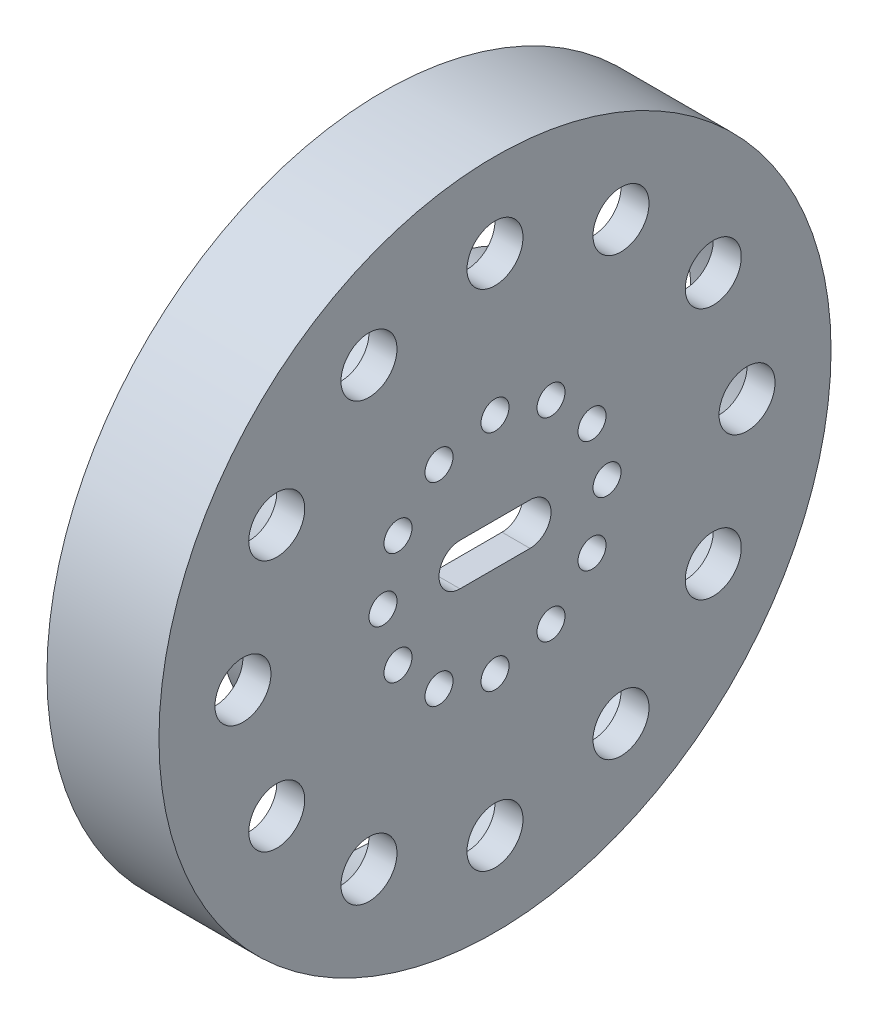
SolidWorks part; units mm, degrees
ref_plane "Front Plane" through (0, 0, 0) normal (0, 0, 1) x (1, 0, 0)
ref_plane "Top Plane" through (0, 0, 0) normal (0, 1, 0) x (1, 0, 0)
ref_plane "Right Plane" through (0, 0, 0) normal (1, 0, 0) x (0, 0, -1)
sketch "Sketch1" plane through (0, 0, 0) normal (0, 0, 1) x (1, 0, 0)
  line L12 (0, 0) -> (0, 76.2)
  line L13 (-25.4, 76.2) -> (0, 76.2)
  line L14 (-6.35, 0) -> (-6.35, 38.1)
  line L15 (-25.4, 69.85) -> (-6.35, 69.85)
  line L16 (-25.4, 69.85) -> (-25.4, 76.2)
  line L17 (-6.35, 0) -> (0, 0)
  line L18 (-6.35, 43.9545) -> (-6.35, 69.85)
  line L19 (-6.35, 43.9545) -> (-19.05, 43.9545)
  line L21 (-6.35, 38.1) -> (-19.05, 38.1)
  line L22 (-19.05, 43.9545) -> (-19.05, 38.1)
  line L23 (-6.35, 0) -> (-6.35, 69.85) construction
  point P11 (-19.05, 41.0272)
  dimension "D1" = 6.35
  dimension "D2" = 19.05
  dimension "D3" = 38.1
  dimension "D4" = 25.4
  dimension "D5" = 76.2
revolve "Revolve" add sketch "Sketch1" angle 360 about L17
sketch "Sketch2" plane through (-6.35, 0, 0) normal (-1, 0, 0) x (0, 0, 1)
  line L0 (0, 0) -> (76.2, 0) construction
  circle A0 centre (0, 0) radius 76.2 construction
  circle A1 centre (0, 0) radius 57.15 construction
  circle A2 centre (57.15, 0) radius 6.35
  circle A3 centre (0, 0) radius 25.4 construction
  circle A4 centre (25.4, 0) radius 3.175
  dimension "D1" = 114.3
  dimension "D2" = 12.7
  dimension "D3" = 50.8
  dimension "D4" = 6.35
extrude "Circular Cut" cut sketch "Sketch2" against normal through all
pattern_circular "CirPattern" count 12 over 360 about axis through (0, 0, 0) along (1, 0, 0) of "Circular Cut"
sketch "Sketch5" plane through (-6.35, 0, 0) normal (-1, 0, 0) x (0, 0, 1)
  line L0 (-7.9375, 0) -> (7.9375, 0) construction
  line L1 (-7.9375, 4.7625) -> (7.9375, 4.7625)
  line L2 (-7.9375, -4.7625) -> (7.9375, -4.7625)
  arc A0 (-7.9375, 4.7625) -> (-7.9375, -4.7625) centre (-7.9375, 0) ccw
  arc A1 (7.9375, -4.7625) -> (7.9375, 4.7625) centre (7.9375, 0) ccw
  point P2 (0, 0)
  dimension "D1" = 15.875
  dimension "D2" = 9.525
extrude "Slot Cut" cut sketch "Sketch5" against normal through all contours A1 L1 A0 L2
